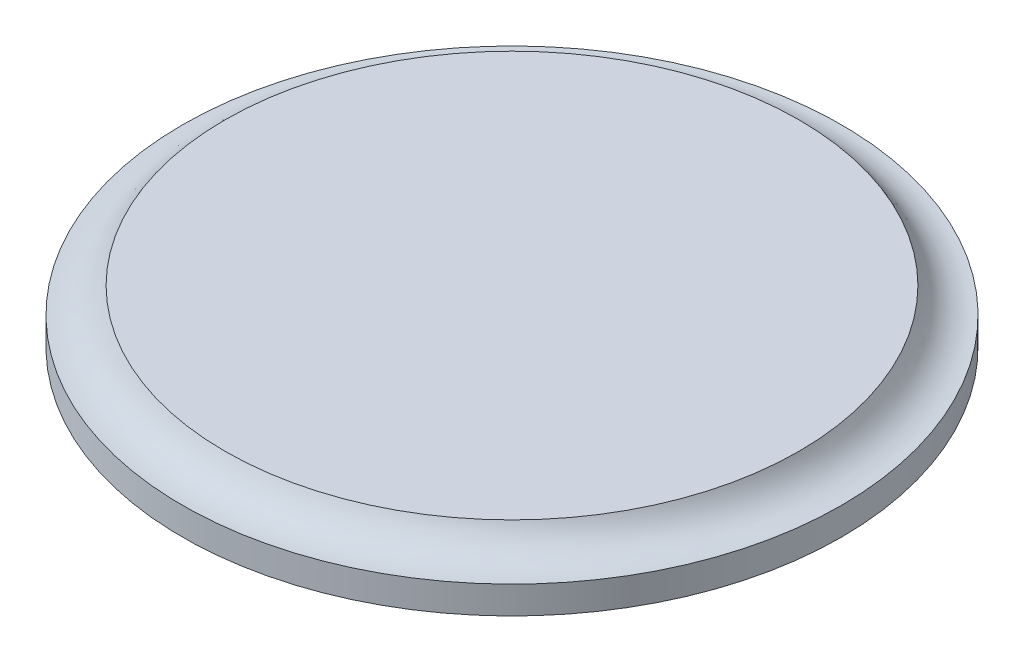
SolidWorks part; units mm, degrees
ref_plane "Front Plane" through (0, 0, 0) normal (0, 0, 1) x (1, 0, 0)
ref_plane "Top Plane" through (0, 0, 0) normal (0, 1, 0) x (1, 0, 0)
ref_plane "Right Plane" through (0, 0, 0) normal (1, 0, 0) x (0, 0, -1)
sketch "Sketch1" plane through (0, 0, 0) normal (0, 0, 1) x (1, 0, 0)
  line L2 (-5, 0) -> (2, 0)
  line L5 (2, 7) -> (2, 0)
  line L7 (-29, 2) -> (2, 2)
  line L8 (-29, 2) -> (-29, 4.5956)
  line L9 (-13.5, 0) -> (2, 0)
  line L10 (-25, 7) -> (2, 7)
  spline S1 degree 2 poles (-29, 4.5956) (-26.2156, 4.4939) (-25, 7) knots 0 0 0 1 1 1
  spline S3 degree 2 poles (-13.5, 0) (-14.3256, 1.7445) (-16.3751, 2) knots 0 0 0 1 1 1
revolve "Revolve1" add sketch "Sketch1" angle 360 about L5
